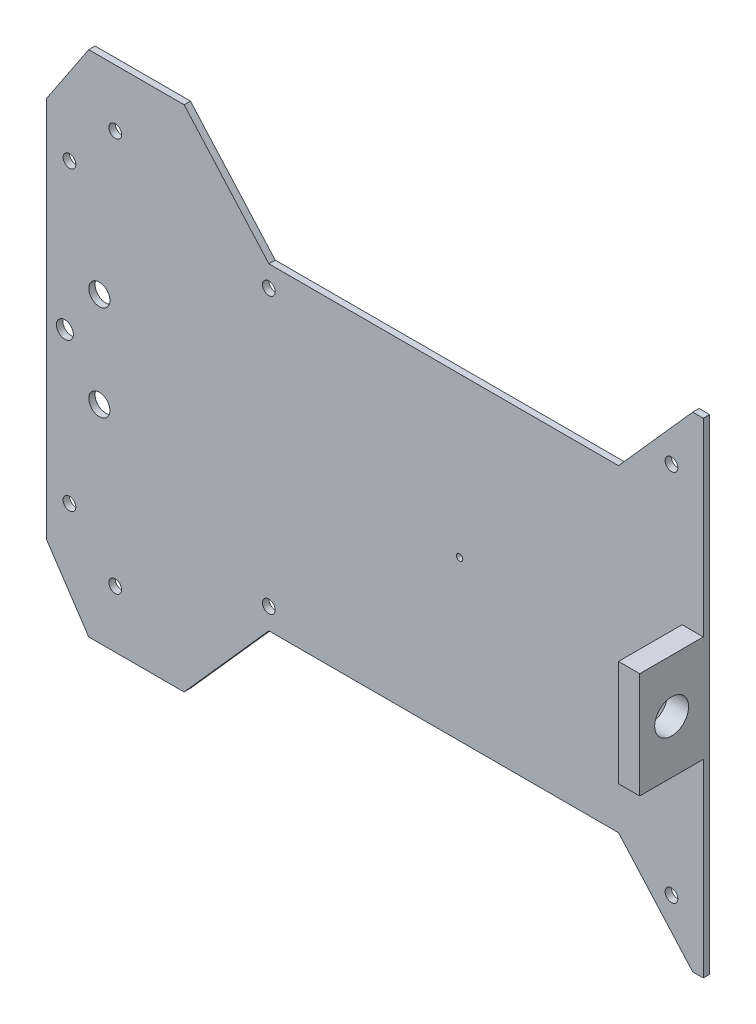
SolidWorks part; units mm, degrees
ref_plane "前视基准面" through (0, 0, 0) normal (0, 0, 1) x (1, 0, 0)
ref_plane "上视基准面" through (0, 0, 0) normal (0, 1, 0) x (1, 0, 0)
ref_plane "右视基准面" through (0, 0, 0) normal (1, 0, 0) x (0, 0, -1)
other "Configuration Table"
sketch "草图1" plane through (0, 0, 0) normal (0, 0, 1) x (1, 0, 0)
  line L0 (0, 0) -> (177289.5009, 0) construction
  line L1 (195, 115) -> (190, 115)
  line L2 (190, 115) -> (190, 120)
  line L3 (0, 0) -> (0, 177289.5009) construction
  line L4 (-175, 120) -> (-175, 90)
  line L5 (-195, 120) -> (195, 120)
  line L6 (-195, 120) -> (-195, -120)
  line L7 (-195, -120) -> (195, -120)
  line L8 (195, 120) -> (195, -120)
  line L9 (-45, 60) -> (45, 60)
  line L10 (-45, 60) -> (-45, -60)
  line L11 (-45, -60) -> (45, -60)
  line L12 (45, 60) -> (45, -60)
  line L13 (-175, 90) -> (-195, 90)
  line L14 (-175, 120) -> (-195, 90)
  line L15 (-175, 120) -> (-130, 120)
  line L16 (190, 120) -> (195, 115)
  line L17 (190, 120) -> (115, 120)
  line L18 (115, 120) -> (115, 75)
  line L19 (115, 75) -> (75, 75)
  line L20 (-130, 120) -> (-130, 75)
  line L21 (-130, 75) -> (-90, 75)
  line L22 (-130, 120) -> (-90, 75)
  line L23 (115, 120) -> (75, 75)
  line L24 (-90, 75) -> (75, 75)
  line L25 (-130, 120) -> (115, 120)
  line L26 (190, -115) -> (190, -120)
  line L27 (195, -115) -> (190, -115)
  line L28 (190, -120) -> (195, -115)
  line L29 (-90, -75) -> (75, -75)
  line L30 (115, -120) -> (115, -75)
  line L31 (115, -75) -> (75, -75)
  line L32 (115, -120) -> (75, -75)
  line L33 (-130, -120) -> (-130, -75)
  line L34 (-130, -75) -> (-90, -75)
  line L35 (-130, -120) -> (-90, -75)
  line L36 (-175, -120) -> (-175, -90)
  line L37 (-175, -90) -> (-195, -90)
  line L38 (-175, -120) -> (-195, -90)
  circle A0 centre (-184.0895, 70) radius 3
  circle A1 centre (104.3795, 93) radius 3
  circle A2 centre (75, 0) radius 10
  circle A3 centre (117.5, 0) radius 7.5
  circle A4 centre (104.3795, -93) radius 3
  circle A5 centre (-184.0895, -70) radius 3
  circle A7 centre (-87, 69) radius 3
  circle A8 centre (-87, -69) radius 3
  point P4 (0, 0)
  point P46 (45, 0)
  dimension "D16" = 6
  dimension "D17" = 6
  dimension "D20" = 20
  dimension "D21" = 30
  dimension "D22" = 42.5
  dimension "D23" = 15
  dimension "D25" = 6
  dimension "D1" = 240
  dimension "D2" = 390
  dimension "D3" = 90
  dimension "D4" = 120
  dimension "D5" = 30
  dimension "D6" = 20
  dimension "D7" = 45
  dimension "D8" = 5
  dimension "D9" = 5
  dimension "D10" = 75
  dimension "D11" = 45
  dimension "D12" = 40
  dimension "D13" = 45
  dimension "D14" = 40
  dimension "D15" = 20
  dimension "D18" = 27
  dimension "D19" = 10
  dimension "D24" = 3
  dimension "D26" = 6
extrude "凸台-拉伸2" add sketch "草图1" along normal blind 3 contours L37 L36 L7 L33 L34 L29 L31 L30 L26 L27 L8 L1 L2 L5 L18 L19 L24 L21 L20 L4 L13 L6 A5 A3 A2 A0 L9 L12 L11 L10 A7 A8 | L22 L20 L21 | L4 L14 L13 | L38 L36 L37 | L33 L35 L34 | L32 L30 L31 A4 | L18 L23 L19 A1 | L16 L2 L1 | L26 L28 L27
sketch "草图2" plane through (0, 0, 3) normal (0, 0, 1) x (1, 0, 0)
  circle A0 centre (117.5, 0) radius 7.5
extrude "凸台-拉伸3" add sketch "草图2" against normal blind 10
sketch "草图3" plane through (0, 0, 3) normal (0, 0, 1) x (1, 0, 0)
  line L0 (115, 120) -> (115, -120)
  line L2 (115, 114.3769) -> (110.0017, 114.3769)
  line L3 (115, 120) -> (75, 75) construction
  line L4 (115, -114.375) -> (110, -114.375)
  line L5 (115, -120) -> (75, -75) construction
  line L6 (110, -114.375) -> (115, -120)
  line L7 (115, 120) -> (110.0017, 114.3769)
  line M8 (75, -75) -> (115, -120)
  line M9 (115, -120) -> (190, -120)
  line M10 (190, -120) -> (195, -115)
  line M11 (195, -115) -> (195, 115)
  line M12 (195, 115) -> (190, 120)
  line M13 (190, 120) -> (115, 120)
  line M14 (115, 120) -> (75, 75)
  dimension "D1" = 5
extrude "切除-拉伸1" cut sketch "草图3" against normal blind 10 contours L0 M13 M9 M10 M11 M12 | L0 L4 M8 | L2 L0 M14
sketch "草图4" plane through (0, 0, 3) normal (0, 0, 1) x (1, 0, 0)
  circle A0 centre (75, 0) radius 10
extrude "凸台-拉伸4" add sketch "草图4" against normal blind 3 contours A0
sketch "草图6" plane through (115, 0, 0) normal (1, 0, 0) x (0, 0, -1)
  line L0 (0, 132) -> (0, -132) construction
  line L1 (7, -7.0711) -> (0, -7.0711)
  line L2 (7, -7.0711) -> (7, 7.0711)
  line L3 (7, 7.0711) -> (0, 7.0711)
  line L4 (0, -7.0711) -> (0, 7.0711)
  line L5 (7, 7.0711) -> (0, 7.0711) construction
extrude "切除-拉伸5" cut sketch "草图6" against normal through all
sketch "草图7" plane through (0, 0, 3) normal (0, 0, 1) x (1, 0, 0)
  line L0 (45, 60) -> (45, -60) construction
  line L1 (-45, 60) -> (45, 60)
  line L2 (-45, 60) -> (-45, -60)
  line L3 (-45, -60) -> (45, -60)
  line L4 (45, 60) -> (45, -60)
extrude "凸台-拉伸5" add sketch "草图7" against normal blind 3
sketch "草图8" plane through (0, 0, 3) normal (0, 0, 1) x (1, 0, 0)
  line L0 (0, 0) -> (50000, 0) construction
  line L1 (0, 0) -> (0, 50000) construction
  line L2 (115, 114.3769) -> (115, -114.375) construction
  line L3 (115, 25) -> (105, 25)
  line L4 (115, 25) -> (115, -25)
  line L5 (115, -25) -> (105, -25)
  line L6 (105, 25) -> (105, -25)
extrude "凸台-拉伸6" add sketch "草图8" along normal blind 30
sketch "草图9" plane through (115, 0, 0) normal (1, 0, 0) x (0, 0, -1)
  line L0 (0, 0) -> (50000, 0) construction
  line L1 (-18, -25) -> (-18, 49975) construction
  line L2 (-33, -25) -> (-3, -25) construction
  circle A0 centre (-17.9316, 0) radius 8
  point P7 (-18, -25)
extrude "切除-拉伸6" cut sketch "草图9" against normal blind 30
sketch "草图10" plane through (0, 0, 3) normal (0, 0, 1) x (1, 0, 0)
  line L0 (104.3795, -96) -> (104.3795, 49904) construction
  line L1 (101.3795, -93) -> (50101.3795, -93) construction
  line L2 (104.3795, 93) -> (50104.3795, 93) construction
  circle A2 centre (104.3795, -93) radius 3
  circle A3 centre (104.3795, 93) radius 3
extrude "凸台-拉伸7" add sketch "草图10" against normal blind 3
sketch "草图11" plane through (0, 0, 3) normal (0, 0, 1) x (1, 0, 0)
  line L0 (0, 0) -> (50000, 0) construction
  line L1 (110, -114.375) -> (75, -75) construction
  line L3 (115, -25) -> (115, -114.375) construction
  circle A0 centre (100, -88.073) radius 3
  circle A1 centre (100, 88.073) radius 3
  dimension "D3" = 6
  dimension "D1" = 10
  dimension "D2" = 15
extrude "切除-拉伸7" cut sketch "草图11" against normal blind 3
sketch "草图12" plane through (0, 0, 3) normal (0, 0, 1) x (1, 0, 0)
  line L0 (0, 0) -> (50000, 0) construction
  line L1 (-87, -69) -> (-87, 49931) construction
  circle A0 centre (-87, 69) radius 3
  circle A1 centre (-87, -69) radius 3
extrude "凸台-拉伸8" add sketch "草图12" against normal blind 3
sketch "草图13" plane through (0, 0, 3) normal (0, 0, 1) x (1, 0, 0)
  line L0 (0, 0) -> (50000, 0) construction
  line L1 (105, 25) -> (105, -25) construction
  line L2 (-90, 75) -> (-90, 50075) construction
  line L3 (75, 75) -> (-90, 75) construction
  circle A0 centre (-90, 65) radius 3
  circle A1 centre (-90, -65) radius 3
  point P5 (105, 0)
  dimension "D1" = 6
  dimension "D2" = 10
extrude "切除-拉伸8" cut sketch "草图13" against normal blind 3
sketch "草图14" plane through (0, 0, 3) normal (0, 0, 1) x (1, 0, 0)
  line L0 (-195, 0) -> (49805, 0) construction
  line L1 (-195, 90) -> (-195, -90) construction
  line L2 (-175, 120) -> (-175, -49880) construction
  line L3 (-162.5, 120) -> (-162.5, 85)
  line L4 (-175, 120) -> (-150, 120)
  line L5 (-175, 120) -> (-175, 85)
  line L6 (-175, 85) -> (-150, 85)
  line L7 (-150, 120) -> (-150, 85)
  circle A0 centre (-162.5, 88) radius 3
  circle A1 centre (-162.5, -88) radius 3
  point P4 (-195, 0)
  dimension "D1" = 35
  dimension "D2" = 25
extrude "切除-拉伸9" cut sketch "草图14" against normal blind 10 contours L3 A0 | L3 A0 | A1
sketch "草图15" plane through (0, 0, 3) normal (0, 0, 1) x (1, 0, 0)
  line L0 (-162.5, -88) -> (-162.5, 49912) construction
  line L1 (-195, 0) -> (49805, 0) construction
  line L2 (-195, 90) -> (-195, -90) construction
  line L3 (-175, -120) -> (-130, -120) construction
  circle A0 centre (-162.5, 88) radius 3
  circle A1 centre (-162.5, -88) radius 3
  circle A2 centre (-162.5, -93) radius 3
  circle A3 centre (-162.5, 93) radius 3
  point P14 (-195, 0)
  circle M3 centre (-162.5, -88) radius 3
  circle M28 centre (-162.5, 88) radius 3
  dimension "D1" = 6
  dimension "D2" = 27
extrude "切除-拉伸10" cut sketch "草图15" against normal through all contours A2 M3 | A3 M28
sketch "草图16" plane through (0, 0, 3) normal (0, 0, 1) x (1, 0, 0)
  line L0 (-162.5, 88) -> (-162.5, 50088) construction
  line L1 (-195, 0) -> (49805, 0) construction
  line L2 (-195, 90) -> (-195, -90) construction
  circle A0 centre (-162.5, 88) radius 3
  circle A1 centre (-162.5, -88) radius 3
  point P7 (-195, 0)
extrude "凸台-拉伸10" add sketch "草图16" against normal blind 3
sketch "草图17" plane through (0, 0, 3) normal (0, 0, 1) x (1, 0, 0)
  line L0 (-162.5, 93) -> (-162.5, 50093) construction
  line L1 (-195, 0) -> (49805, 0) construction
  line L2 (-195, 90) -> (-195, -90) construction
  circle A0 centre (-162.5, 93) radius 3
  circle A1 centre (-162.5, -93) radius 3
  point P7 (-195, 0)
extrude "切除-拉伸11" cut sketch "草图17" against normal through all
sketch "草图18" plane through (0, 0, 3) normal (0, 0, 1) x (1, 0, 0)
  line L0 (-195, 0) -> (49805, 0) construction
  line L1 (-195, 90) -> (-195, -90) construction
  line L2 (-180, 30) -> (-180, -30)
  line L3 (-195, 30) -> (-150, 30)
  line L4 (-195, 30) -> (-195, -30)
  line L5 (-195, -30) -> (-150, -30)
  line L6 (-150, 30) -> (-150, -30)
  circle A0 centre (-170, 22.5) radius 5
  circle A1 centre (-170, -22.5) radius 5
  point P4 (-195, 0)
  dimension "D2" = 7.5
  dimension "D1" = 15
  dimension "D3" = 10
extrude "切除-拉伸12" cut sketch "草图18" against normal blind 10 contours A0 | A1
sketch "草图20" plane through (0, 0, 3) normal (0, 0, 1) x (1, 0, 0)
  line L0 (0, 0) -> (0, 50000) construction
  line L1 (0, 0) -> (50000, 0) construction
  circle A0 centre (0, 0) radius 1.5
extrude "切除-拉伸13" cut sketch "草图20" against normal blind 10
sketch "草图21" plane through (0, 0, 3) normal (0, 0, 1) x (1, 0, 0)
  line L0 (-195, 0) -> (49805, 0) construction
  line L1 (-195, 90) -> (-195, -90) construction
  line L2 (-170, 22.5) -> (-170, 50022.5) construction
  line L3 (-186.25, 35.6208) -> (-186.25, -29.8583)
  circle A0 centre (-186.25, 0) radius 4
  point P4 (-195, 0)
  dimension "D1" = 16.25
extrude "切除-拉伸14" cut sketch "草图21" against normal blind 10 contours L3 A0 | L3 A0
